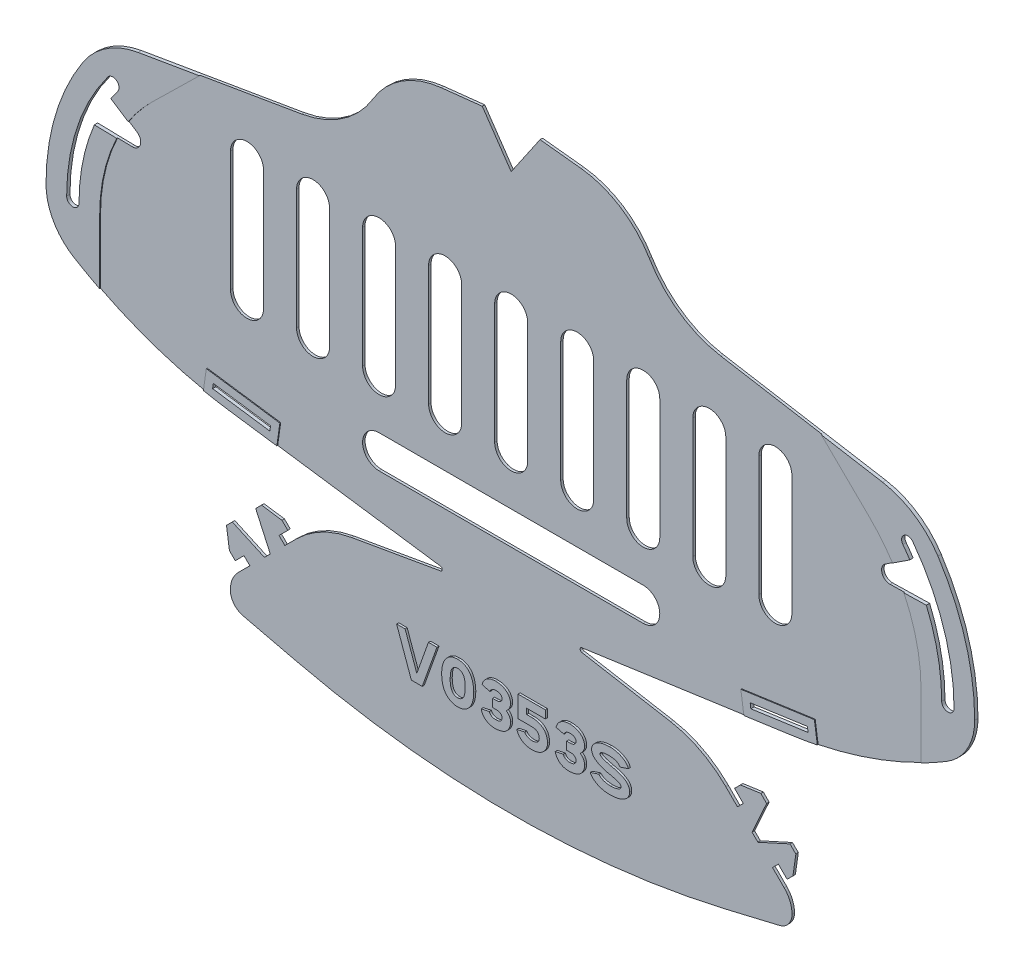
SolidWorks part; units mm, degrees
ref_plane "Front Plane" through (0, 0, 0) normal (0, 0, 1) x (1, 0, 0)
ref_plane "Top Plane" through (0, 0, 0) normal (0, 1, 0) x (1, 0, 0)
ref_plane "Right Plane" through (0, 0, 0) normal (1, 0, 0) x (0, 0, -1)
sketch "Sketch1" plane through (0, 0, 0) normal (0, 0, 1) x (1, 0, 0)
  line L0 (0, 0) -> (0, -145) construction
  line L1 (-14, -102) -> (14, -102) construction
  line L2 (-112.5, -69) -> (112.5, -69) construction
  line L3 (0, -10.2352) -> (-7, 0)
  line L4 (0, -10.2352) -> (7, 0)
  line L5 (7, 0) -> (16.9419, -1.0768)
  line L6 (-90.1804, -30.1909) -> (-50.7439, -23.5)
  line L7 (90.1804, -30.1909) -> (50.7439, -23.5)
  line L8 (-14, -102) -> (-68.2662, -94.2919)
  line L9 (-7, 0) -> (-16.9419, -1.0768)
  line L10 (14, -102) -> (68.2662, -94.2919)
  line L11 (-103.5977, -39) -> (-103.5977, -69) construction
  line L12 (-14, -102) -> (-38.6266, -106.305)
  line L13 (-52, -113.2546) -> (-54.8283, -116.0832)
  line L14 (52, -113.2546) -> (54.8283, -116.0832)
  line L15 (14, -102) -> (38.6266, -106.305)
  line L16 (-54.8283, -116.0832) -> (-56.2426, -114.669)
  line L17 (-56.2426, -114.669) -> (-54.1214, -112.5476)
  line L18 (-54.1214, -112.5476) -> (-55.5356, -111.1334)
  line L19 (-55.5356, -111.1334) -> (-60.4854, -110.4265)
  line L20 (-60.4854, -110.4265) -> (-68.9703, -118.9122)
  line L21 (-64.7275, -123.1546) -> (-63.3132, -124.5688)
  line L22 (-63.3132, -124.5688) -> (-66.1415, -127.3973)
  line L23 (-64.7275, -123.1546) -> (-66.8487, -125.2761)
  line L24 (-66.8487, -125.2761) -> (-68.263, -123.8619)
  line L25 (-68.9703, -118.9122) -> (-68.263, -123.8619)
  line L26 (68.9703, -118.9122) -> (68.263, -123.8619)
  line L27 (66.8487, -125.2761) -> (68.263, -123.8619)
  line L28 (64.7275, -123.1546) -> (66.8487, -125.2761)
  line L29 (63.3132, -124.5688) -> (66.1415, -127.3973)
  line L30 (64.7275, -123.1546) -> (63.3132, -124.5688)
  line L31 (60.4854, -110.4265) -> (68.9703, -118.9122)
  line L32 (55.5356, -111.1334) -> (60.4854, -110.4265)
  line L33 (54.1214, -112.5476) -> (55.5356, -111.1334)
  line L34 (56.2426, -114.669) -> (54.1214, -112.5476)
  line L35 (54.8283, -116.0832) -> (56.2426, -114.669)
  line L36 (-64.9691, -135.8852) -> (-52.4361, -138.8607)
  line L37 (64.9691, -135.8852) -> (52.4361, -138.8607)
  line L38 (-68.9703, -118.9122) -> (-64.7275, -123.1546) construction
  line L39 (-60.4854, -110.4265) -> (-56.2426, -114.669) construction
  arc A0 (-16.9419, -1.0768) -> (-33.4614, -11.6696) centre (-14.5729, -22.9489) ccw
  arc A1 (-33.4614, -11.6696) -> (-50.7439, -23.5) centre (-54.9257, 1.1478) cw
  arc A2 (-103.5977, -39) -> (-90.1804, -30.1909) centre (-86.8349, -49.9091) cw
  arc A3 (-112.5, -69) -> (-103.5977, -39) centre (-57.5, -69) cw
  arc A4 (112.5, -69) -> (103.5977, -39) centre (57.5, -69) ccw
  arc A5 (103.5977, -39) -> (90.1804, -30.1909) centre (86.8349, -49.9091) ccw
  arc A6 (16.9419, -1.0768) -> (33.4614, -11.6696) centre (14.5729, -22.9489) cw
  arc A7 (33.4614, -11.6696) -> (50.7439, -23.5) centre (54.9257, 1.1478) ccw
  arc A8 (-112.5, -69) -> (-105.7111, -81) centre (-98.5, -69) ccw
  arc A9 (-105.7111, -81) -> (-68.2662, -94.2919) centre (-54.2032, 4.7143) ccw
  arc A10 (112.5, -69) -> (105.7111, -81) centre (98.5, -69) cw
  arc A11 (105.7111, -81) -> (68.2662, -94.2919) centre (54.2032, 4.7143) cw
  arc A12 (-38.6266, -106.305) -> (-52, -113.2546) centre (-34.3216, -130.9315) ccw
  arc A13 (38.6266, -106.305) -> (52, -113.2546) centre (34.3216, -130.9315) cw
  arc A14 (-66.1415, -127.3973) -> (-68.0451, -131.9933) centre (-61.5451, -131.9933) ccw
  arc A15 (-68.0451, -131.9933) -> (-64.9691, -135.8852) centre (-64.0451, -131.9933) ccw
  arc A16 (68.0451, -131.9933) -> (64.9691, -135.8852) centre (64.0451, -131.9933) cw
  arc A17 (66.1415, -127.3973) -> (68.0451, -131.9933) centre (61.5451, -131.9933) cw
  arc A19 (-52.4361, -138.8607) -> (0, -145) centre (0, 82) ccw
  arc A20 (52.4361, -138.8607) -> (0, -145) centre (0, 82) cw
  point P8 (0, -102)
  point P11 (0, -69)
  dimension "D5" = 55
  dimension "D11" = 20
  dimension "D13" = 25
  dimension "D16" = 14
  dimension "D15" = 22
  dimension "D18" = 100
  dimension "D22" = 25
  dimension "D31" = 6.5
  dimension "D32" = 4
  dimension "D34" = 227
  dimension "D1" = 145
  dimension "D2" = 28
  dimension "D3" = 43
  dimension "D4" = 76
  dimension "D6" = 225
  dimension "D7" = 14
  dimension "D8" = 12.4
  dimension "D9" = 10
  dimension "D10" = 30
  dimension "D12" = 40
  dimension "D14" = 45.5
  dimension "D17" = 12
  dimension "D19" = 18
  dimension "D20" = 25
  dimension "D21" = 4
  dimension "D23" = 38
  dimension "D24" = 2
  dimension "D25" = 3
  dimension "D26" = 2
  dimension "D27" = 18
  dimension "D29" = 8
  dimension "D30" = 4
extrude "Main Shape" add sketch "Sketch1" along normal blind 0.6
sketch "Sketch2" plane through (0, 0, 0.6) normal (0, 0, 1) x (1, 0, 0)
  line L0 (0, -55) -> (0, 55) construction
  arc A0 (-96.3, -39.9) -> (-106, -69) centre (-57.5, -69) ccw construction
  arc A1 (-97.5, -39) -> (-107.5, -69) centre (-57.5, -69) ccw
  arc A2 (-95.1, -40.8) -> (-104.5, -69) centre (-57.5, -69) ccw
  arc A3 (-95.1, -40.8) -> (-97.5, -39) centre (-96.3, -39.9) ccw
  arc A4 (-107.5, -69) -> (-104.5, -69) centre (-106, -69) ccw
  arc A6 (-103.5977, -39) -> (-112.5, -69) centre (-57.5, -69) ccw construction
  arc A7 (96.3, -39.9) -> (106, -69) centre (57.5, -69) cw construction
  arc A8 (97.5, -39) -> (107.5, -69) centre (57.5, -69) cw
  arc A9 (95.1, -40.8) -> (104.5, -69) centre (57.5, -69) cw
  arc A10 (95.1, -40.8) -> (97.5, -39) centre (96.3, -39.9) cw
  arc A11 (107.5, -69) -> (104.5, -69) centre (106, -69) cw
  point P3 (-103.5111, -53.663)
  point P19 (103.5111, -53.663)
  dimension "D1" = 5
  dimension "D2" = 1.5
extrude "Elastic Attachment Points" cut sketch "Sketch2" against normal through all
sketch "Sketch7" plane through (0, 0, 0.6) normal (0, 0, 1) x (1, 0, 0)
  line L0 (-99.5, -69) -> (-99.5, -84.4384)
  line L1 (-86.8939, -39) -> (-75.3319, -27.6717)
  line L2 (-50.7439, -23.5) -> (-90.1804, -30.1909) construction
  line L3 (-75.3319, -27.6717) -> (-90.1804, -30.1909)
  line L4 (0, -55) -> (0, 55) construction
  line L5 (75.3319, -27.6717) -> (90.1804, -30.1909)
  line L6 (86.8939, -39) -> (75.3319, -27.6717)
  line L7 (99.5, -69) -> (99.5, -84.4384)
  arc A0 (-99.5, -69) -> (-86.8939, -39) centre (-57.5, -69) cw
  arc A1 (-95.1, -40.8) -> (-104.5, -69) centre (-57.5, -69) ccw construction
  arc A2 (-105.7111, -81) -> (-68.2662, -94.2919) centre (-54.2032, 4.7143) ccw construction
  arc A3 (-112.5, -69) -> (-105.7111, -81) centre (-98.5, -69) ccw construction
  arc A4 (-103.5977, -39) -> (-112.5, -69) centre (-57.5, -69) ccw construction
  arc A5 (-90.1804, -30.1909) -> (-103.5977, -39) centre (-86.8349, -49.9091) ccw construction
  arc A6 (-105.7111, -81) -> (-99.5, -84.4384) centre (-54.2032, 4.7143) ccw
  arc A7 (-112.5, -69) -> (-105.7111, -81) centre (-98.5, -69) ccw
  arc A8 (-103.5977, -39) -> (-112.5, -69) centre (-57.5, -69) ccw
  arc A9 (-90.1804, -30.1909) -> (-103.5977, -39) centre (-86.8349, -49.9091) ccw
  arc A10 (90.1804, -30.1909) -> (103.5977, -39) centre (86.8349, -49.9091) cw
  arc A11 (103.5977, -39) -> (112.5, -69) centre (57.5, -69) cw
  arc A12 (112.5, -69) -> (105.7111, -81) centre (98.5, -69) cw
  arc A13 (105.7111, -81) -> (99.5, -84.4384) centre (54.2032, 4.7143) cw
  arc A14 (99.5, -69) -> (86.8939, -39) centre (57.5, -69) ccw
  arc A15 (-107.5, -69) -> (-104.5, -69) centre (-106, -69) ccw construction
  arc A16 (-95.1, -40.8) -> (-97.5, -39) centre (-96.3, -39.9) ccw construction
  arc A17 (-97.5, -39) -> (-107.5, -69) centre (-57.5, -69) ccw construction
  arc A18 (-107.5, -69) -> (-104.5, -69) centre (-106, -69) ccw
  arc A19 (-95.1, -40.8) -> (-97.5, -39) centre (-96.3, -39.9) ccw
  arc A20 (-95.1, -40.8) -> (-104.5, -69) centre (-57.5, -69) ccw
  arc A21 (-97.5, -39) -> (-107.5, -69) centre (-57.5, -69) ccw
  arc A22 (104.5, -69) -> (107.5, -69) centre (106, -69) ccw construction
  arc A23 (97.5, -39) -> (95.1, -40.8) centre (96.3, -39.9) ccw construction
  arc A24 (104.5, -69) -> (95.1, -40.8) centre (57.5, -69) ccw construction
  arc A25 (107.5, -69) -> (97.5, -39) centre (57.5, -69) ccw construction
  arc A26 (104.5, -69) -> (107.5, -69) centre (106, -69) ccw
  arc A27 (97.5, -39) -> (95.1, -40.8) centre (96.3, -39.9) ccw
  arc A28 (104.5, -69) -> (95.1, -40.8) centre (57.5, -69) ccw
  arc A29 (107.5, -69) -> (97.5, -39) centre (57.5, -69) ccw
  dimension "D1" = 5
extrude "Reinforced Attachment Points" add sketch "Sketch7" along normal blind 0.2
sketch "Sketch6" plane through (0, 0, 0.6) normal (0, 0, 1) x (1, 0, 0)
  line L0 (-72.1324, -91.7227) -> (-58.2715, -93.6915)
  line L1 (-58.2715, -93.6915) -> (-58.1028, -92.5034)
  line L2 (-58.1028, -92.5034) -> (-71.9637, -90.5346)
  line L3 (-71.9637, -90.5346) -> (-72.1324, -91.7227)
  line L4 (-68.2662, -94.2919) -> (-14, -102) construction
  line L5 (-65.0332, -91.519) -> (-65.202, -92.7071) construction
  line L13 (0, -0.44) -> (0, 0.44) construction
  line L14 (65.0332, -91.519) -> (65.202, -92.7071) construction
  line L15 (72.1324, -91.7227) -> (71.9637, -90.5346)
  line L16 (58.1028, -92.5034) -> (58.2715, -93.6915)
  line L22 (58.1028, -92.5034) -> (71.9637, -90.5346)
  line L24 (72.1324, -91.7227) -> (58.2715, -93.6915)
  dimension "D1" = 2
  dimension "D2" = 14
  dimension "D3" = 52
  dimension "D4" = 1.2
extrude "Tab Slits" cut sketch "Sketch6" against normal through all
sketch "Sketch9" plane through (0, 0, 0.6) normal (0, 0, 1) x (1, 0, 0)
  line L4 (-58.2715, -93.6915) -> (-58.1028, -92.5034) construction
  line L5 (-72.1324, -91.7227) -> (-58.2715, -93.6915) construction
  line L6 (-71.9637, -90.5346) -> (-72.1324, -91.7227) construction
  line L7 (-58.1028, -92.5034) -> (-71.9637, -90.5346) construction
  line L12 (-58.2715, -93.6915) -> (-58.1028, -92.5034)
  line L13 (-72.1324, -91.7227) -> (-58.2715, -93.6915)
  line L14 (-71.9637, -90.5346) -> (-72.1324, -91.7227)
  line L15 (-58.1028, -92.5034) -> (-71.9637, -90.5346)
  line L16 (-56.5727, -95.9529) -> (-55.8414, -90.8046)
  line L17 (-68.2662, -94.2919) -> (-14, -102) construction
  line L18 (-55.8414, -90.8046) -> (-73.6625, -88.2732)
  line L19 (-73.6625, -88.2732) -> (-74.3668, -93.2318)
  line L20 (-68.2662, -94.2919) -> (-56.5727, -95.9529)
  line L21 (0, -0.44) -> (0, 0.44) construction
  line L22 (68.2662, -94.2919) -> (56.5727, -95.9529)
  line L23 (73.6625, -88.2732) -> (74.3668, -93.2318)
  line L24 (55.8414, -90.8046) -> (73.6625, -88.2732)
  line L25 (56.5727, -95.9529) -> (55.8414, -90.8046)
  line L26 (58.1028, -92.5034) -> (71.9637, -90.5346)
  line L27 (71.9637, -90.5346) -> (72.1324, -91.7227)
  line L28 (72.1324, -91.7227) -> (58.2715, -93.6915)
  line L29 (58.2715, -93.6915) -> (58.1028, -92.5034)
  arc A0 (-99.5, -84.4384) -> (-68.2662, -94.2919) centre (-54.2032, 4.7143) ccw construction
  arc A1 (-74.3668, -93.2318) -> (-68.2662, -94.2919) centre (-54.2032, 4.7143) ccw
  arc A2 (74.3668, -93.2318) -> (68.2662, -94.2919) centre (54.2032, 4.7143) cw
  dimension "D1" = 2
  dimension "D2" = 2
  dimension "D3" = 2
extrude "Reinforced Tab Slits" add sketch "Sketch9" along normal blind 0.2
sketch "Sketch11" plane through (0, 0, 0.6) normal (0, 0, 1) x (1, 0, 0)
  line L0 (-67.5562, -117.4979) -> (-59.7778, -121.0331)
  line L1 (-60.4854, -110.4265) -> (-68.9703, -118.9122) construction
  line L2 (-59.7778, -121.0331) -> (-58.3637, -119.6188)
  line L3 (-58.3637, -119.6188) -> (-61.8996, -111.8408)
  line L4 (-61.8996, -111.8408) -> (-67.5562, -117.4979)
  line L6 (-58.3637, -119.6188) -> (-54.8283, -116.0832) construction
  line L7 (-59.7778, -121.0331) -> (-63.3132, -124.5688) construction
  line L10 (0, -0.44) -> (0, 0.44) construction
  line L11 (59.7778, -121.0331) -> (63.3132, -124.5688) construction
  line L12 (58.3637, -119.6188) -> (54.8283, -116.0832) construction
  line L13 (61.8996, -111.8408) -> (67.5562, -117.4979)
  line L14 (58.3637, -119.6188) -> (61.8996, -111.8408)
  line L15 (59.7778, -121.0331) -> (58.3637, -119.6188)
  line L16 (67.5562, -117.4979) -> (59.7778, -121.0331)
  dimension "D1" = 2
  dimension "D2" = 2
  dimension "D3" = 5
extrude "Tab Flex Relief" cut sketch "Sketch11" against normal through all both and the other way through all
sketch "Sketch3" plane through (0, 0, 0.6) normal (0, 0, 1) x (1, 0, 0)
  line L3 (0, -10.2352) -> (0, -145) construction
  line L4 (-106, -69) -> (-96.3, -69) construction
  line L5 (-96.3, -69) -> (-96.3, -39.9) construction
  line L427 (0, -39.9) -> (0, -69) construction
  line L428 (4, -39.9) -> (4, -69)
  line L429 (-4, -39.9) -> (-4, -69)
  line L444 (-16, -39.9) -> (-16, -69) construction
  line L447 (-12, -39.9) -> (-12, -69)
  line L450 (-20, -39.9) -> (-20, -69)
  line L451 (-32, -39.9) -> (-32, -69) construction
  line L455 (-28, -39.9) -> (-28, -69)
  line L456 (-36, -39.9) -> (-36, -69)
  line L836 (-32, -85) -> (32, -85) construction
  line L837 (-32, -81) -> (32, -81)
  line L838 (-32, -89) -> (32, -89)
  line L839 (-64, -73) -> (64, -73) construction
  line L933 (-48, -39.9) -> (-48, -69) construction
  line L934 (-44, -39.9) -> (-44, -69)
  line L935 (-52, -39.9) -> (-52, -69)
  line L936 (-64, -39.9) -> (-64, -69) construction
  line L937 (-60, -39.9) -> (-60, -69)
  line L938 (-68, -39.9) -> (-68, -69)
  line L939 (16, -39.9) -> (16, -69) construction
  line L940 (12, -39.9) -> (12, -69)
  line L941 (20, -39.9) -> (20, -69)
  line L942 (32, -39.9) -> (32, -69) construction
  line L943 (28, -39.9) -> (28, -69)
  line L944 (36, -39.9) -> (36, -69)
  line L945 (48, -39.9) -> (48, -69) construction
  line L946 (44, -39.9) -> (44, -69)
  line L947 (52, -39.9) -> (52, -69)
  line L948 (64, -39.9) -> (64, -69) construction
  line L949 (60, -39.9) -> (60, -69)
  line L950 (68, -39.9) -> (68, -69)
  arc A2 (-52.4361, -138.8607) -> (52.4361, -138.8607) centre (0, 82) ccw construction
  arc A21 (4, -39.9) -> (-4, -39.9) centre (0, -39.9) ccw
  arc A22 (-4, -69) -> (4, -69) centre (0, -69) ccw
  arc A23 (-12, -39.9) -> (-20, -39.9) centre (-16, -39.9) ccw
  arc A24 (-20, -69) -> (-12, -69) centre (-16, -69) ccw
  arc A25 (-28, -39.9) -> (-36, -39.9) centre (-32, -39.9) ccw
  arc A26 (-36, -69) -> (-28, -69) centre (-32, -69) ccw
  arc A27 (-44, -39.9) -> (-52, -39.9) centre (-48, -39.9) ccw
  arc A28 (-52, -69) -> (-44, -69) centre (-48, -69) ccw
  arc A29 (-60, -39.9) -> (-68, -39.9) centre (-64, -39.9) ccw
  arc A30 (-68, -69) -> (-60, -69) centre (-64, -69) ccw
  arc A31 (12, -39.9) -> (20, -39.9) centre (16, -39.9) cw
  arc A32 (20, -69) -> (12, -69) centre (16, -69) cw
  arc A33 (28, -39.9) -> (36, -39.9) centre (32, -39.9) cw
  arc A34 (36, -69) -> (28, -69) centre (32, -69) cw
  arc A35 (44, -39.9) -> (52, -39.9) centre (48, -39.9) cw
  arc A36 (52, -69) -> (44, -69) centre (48, -69) cw
  arc A37 (60, -39.9) -> (68, -39.9) centre (64, -39.9) cw
  arc A38 (68, -69) -> (60, -69) centre (64, -69) cw
  arc A39 (-32, -81) -> (-32, -89) centre (-32, -85) ccw
  arc A40 (32, -89) -> (32, -81) centre (32, -85) ccw
  point P3 (-16, -54.45)
  point P18 (-32, -54.45)
  point P30 (-48, -54.45)
  point P37 (-64, -54.45)
  point P43 (16, -54.45)
  point P50 (32, -54.45)
  point P57 (48, -54.45)
  point P64 (64, -54.45)
  point P71 (0, -85)
  point P414 (0, -54.45)
  dimension "D5" = 8
  dimension "D1" = 8
  dimension "D2" = 5
  dimension "D3" = 8
  dimension "D4" = 8
extrude "Breathing Slits" cut sketch "Sketch3" against normal through all
sketch "Sketch8" plane through (0, 0, 0.6) normal (0, 0, 1) x (1, 0, 0)
  line L0 (-67.0266, -128.5) -> (67.0266, -128.5) construction
  line L1 (0, -10.2352) -> (0, -145) construction
  arc A0 (-52.4361, -138.8607) -> (52.4361, -138.8607) centre (0, 82) ccw construction
  arc A1 (-66.1415, -127.3973) -> (-68.0451, -131.9933) centre (-61.5451, -131.9933) ccw construction
  text T0 "<b>V0353S</b>\r\n" font "Double Porter 3" height 10
  point P9 (0, -128.5)
  dimension "D2" = 16.5
extrude "Version Number" add sketch "Sketch8" along normal blind 0.5
fillet "Fillet1" radius 0.5 2 edges at (-14, -102, 0.3) (14, -102, 0.3)
sketch "Sketch12" plane through (0, 0, 0.8) normal (0, 0, 1) x (1, 0, 0)
  line L0 (-96.7835, -43.1968) -> (-90.6474, -47.2273)
  line L1 (-96.7835, -43.1968) -> (-87.9974, -29.8205) construction
  line L2 (-75.3319, -27.6717) -> (-90.1804, -30.1909) construction
  line L3 (-100.7885, -50.6941) -> (-91.7908, -50.8984)
  line L4 (0, -0.44) -> (0, 0.44) construction
  line L5 (96.7835, -43.1968) -> (87.9974, -29.8205) construction
  line L6 (100.7885, -50.6941) -> (91.7908, -50.8984)
  line L7 (96.7835, -43.1968) -> (90.6474, -47.2273)
  arc A0 (-95.1, -40.8) -> (-104.5, -69) centre (-57.5, -69) ccw construction
  arc A1 (-91.7908, -50.8984) -> (-90.6474, -47.2273) centre (-91.7454, -48.8989) ccw
  arc A2 (-96.7835, -43.1968) -> (-100.7885, -50.6941) centre (-57.5, -69) ccw
  arc A3 (96.7835, -43.1968) -> (100.7885, -50.6941) centre (57.5, -69) cw
  arc A4 (91.7908, -50.8984) -> (90.6474, -47.2273) centre (91.7454, -48.8989) cw
  dimension "D4" = 2
  dimension "D1" = 25.8032
  dimension "D2" = 8.5
  dimension "D3" = 9
extrude "Cut-Extrude1" cut sketch "Sketch12" against normal through all both and the other way through all
